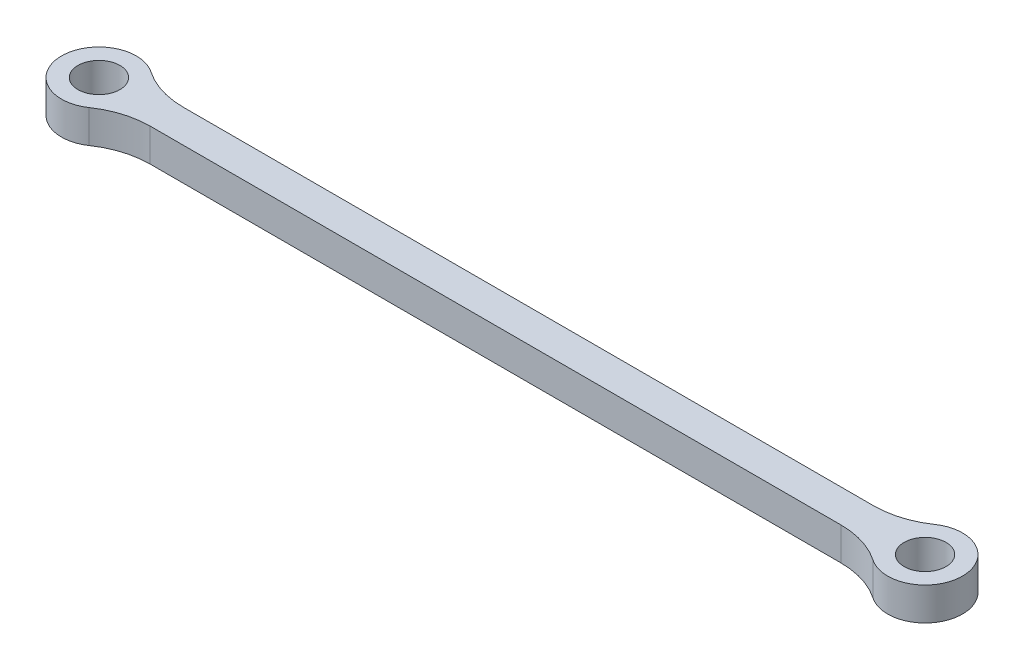
SolidWorks part; units mm, degrees
material "PLA 100% Infill"
ref_plane "Front Plane" through (0, 0, 0) normal (0, 0, 1) x (1, 0, 0)
ref_plane "Top Plane" through (0, 0, 0) normal (0, 1, 0) x (1, 0, 0)
ref_plane "Right Plane" through (0, 0, 0) normal (1, 0, 0) x (0, 0, -1)
sketch "Sketch1" plane through (0, 0, 0) normal (0, 1, 0) x (1, 0, 0)
  line L0 (0, 0) -> (-100.4, 0) construction
  line L1 (0, 2) -> (-100.4, 2)
  line L2 (0, -2) -> (-100.4, -2)
  circle A0 centre (-100.4, 0) radius 2.55
  circle A1 centre (0, 0) radius 2.55
  circle A2 centre (-100.4, 0) radius 4.55
  circle A3 centre (0, 0) radius 4.55
  circle A4 centre (-100.4, 0) radius 0.55
  circle A5 centre (0, 0) radius 0.55
  dimension "D1" = 5.1
  dimension "D2" = 100.4
  dimension "D3" = 2
  dimension "D4" = 2
  dimension "D5" = 2
  dimension "D6" = 2
extrude "Boss-Extrude1" add sketch "Sketch1" along normal blind 4 contours L1 A2 L2 A0 | A3 L0 A2 L2 | L0 A3 L1 A2 | L0 A2 L1 A0 | A2 L0 A0 L2 | L2 A3 L1 A1 | L0 A1 L1 A3 | A1 L0 A3 L2
fillet "Fillet1" radius 10 4 edges at (-96.3131, 2, -2) (-4.0869, 2, -2) (-4.0869, 2, 2) (-96.3131, 2, 2)
